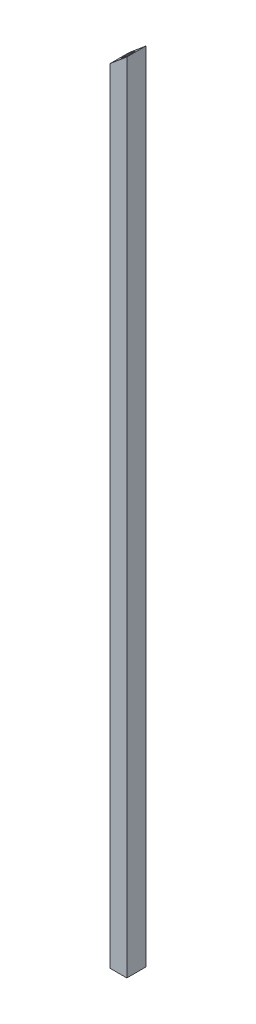
SolidWorks part; units mm, degrees
ref_plane "Front Plane" through (0, 0, 0) normal (0, 0, 1) x (1, 0, 0)
ref_plane "Top Plane" through (0, 0, 0) normal (0, 1, 0) x (1, 0, 0)
ref_plane "Right Plane" through (0, 0, 0) normal (1, 0, 0) x (0, 0, -1)
sketch "Sketch2" plane through (0, 0, 0) normal (0, 0, 1) x (1, 0, 0)
  line L1 (-11.1125, -533.4) -> (11.1125, -533.4)
  line L2 (-11.1125, -533.4) -> (-11.1125, 533.4)
  line L3 (-11.1125, 533.4) -> (11.1125, 533.4)
  line L4 (11.1125, -533.4) -> (11.1125, 533.4)
  line L5 (-11.1125, -533.4) -> (11.1125, 533.4) construction
  line L6 (-11.1125, 533.4) -> (11.1125, -533.4) construction
  point P0 (0, 0)
  dimension "D1" = 1066.8
extrude "Boss-Extrude1" add sketch "Sketch2" along normal mid plane 25.4
sketch "Sketch3" plane through (0, 533.4, 0) normal (0, 1, 0) x (1, 0, 0)
  line L8 (4.7625, 6.35) -> (-4.7625, 6.35)
  line L9 (-4.7625, 6.35) -> (-4.7625, -6.35)
  line L10 (-4.7625, -6.35) -> (4.7625, -6.35)
  line L11 (4.7625, -6.35) -> (4.7625, 6.35)
  line L12 (4.7625, 6.35) -> (-4.7625, 6.35)
  line L13 (-4.7625, 6.35) -> (-4.7625, -6.35)
  line L14 (-4.7625, -6.35) -> (4.7625, -6.35)
  line L15 (4.7625, -6.35) -> (4.7625, 6.35)
  dimension "D1" = 6.35
extrude "Cut-Extrude1" cut sketch "Sketch3" against normal through all
sketch "Sketch4" plane through (0, 0, 12.7) normal (0, 0, 1) x (1, 0, 0)
  line L0 (11.1125, 533.4) -> (-11.1125, 514.751)
  line L1 (-11.1125, 533.4) -> (-11.1125, -533.4) construction
  line L2 (11.1125, -533.4) -> (11.1125, 533.4) construction
  line L3 (-11.1125, 514.751) -> (-11.1125, 533.4)
  line L4 (-11.1125, 533.4) -> (11.1125, 533.4)
  dimension "D1" = 50
extrude "Cut-Extrude2" cut sketch "Sketch4" against normal through all
